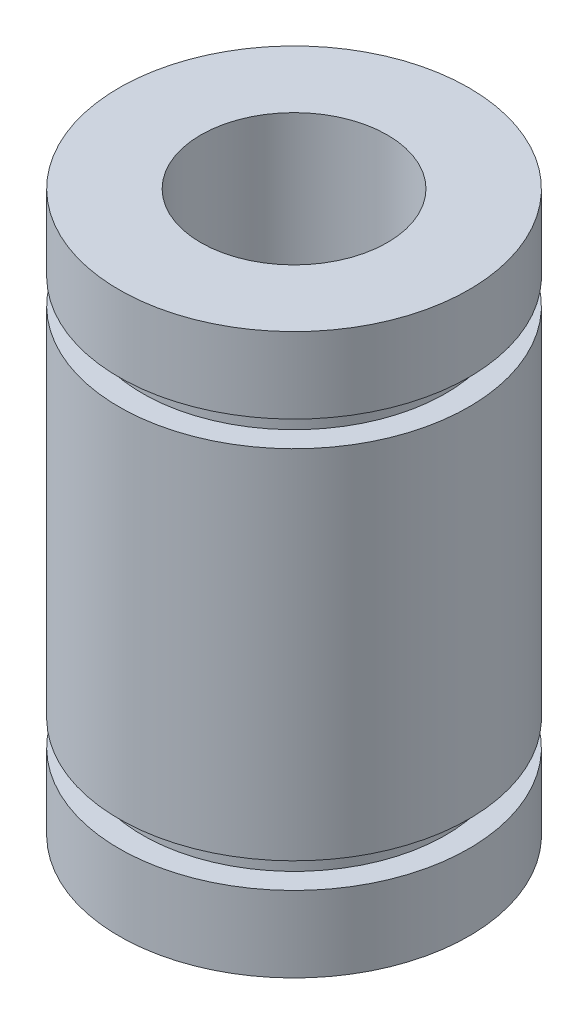
SolidWorks part; units mm, degrees
material "Plain Carbon Steel"
ref_plane "Front Plane" through (0, 0, 0) normal (0, 0, 1) x (1, 0, 0)
ref_plane "Top Plane" through (0, 0, 0) normal (0, 1, 0) x (1, 0, 0)
ref_plane "Right Plane" through (0, 0, 0) normal (1, 0, 0) x (0, 0, -1)
sketch "Sketch1" plane through (0, 0, 0) normal (0, 0, 1) x (1, 0, 0)
  line L0 (4, 0) -> (4, 12)
  line L1 (4, 12) -> (7.5, 12)
  line L2 (7.5, 12) -> (7.5, 8.75)
  line L3 (7.5, 8.75) -> (6.5, 8.75)
  line L4 (6.5, 8.75) -> (6.5, 7.65)
  line L8 (6.5, 7.65) -> (7.5, 7.65)
  line L9 (7.5, 7.65) -> (7.5, 0)
  line L10 (4, 0) -> (7.5, 0)
  line L11 (0, 0) -> (0, 12) construction
  dimension "D1" = 12
  dimension "D2" = 4
  dimension "D3" = 3.5
  dimension "D4" = 3.25
  dimension "D5" = 1.1
  dimension "D6" = 1
revolve "Revolve1" add sketch "Sketch1" angle 360 about L11
mirror "Mirror1" about plane through (4, 0, 0) normal (0, -1, 0) of "Revolve1"
